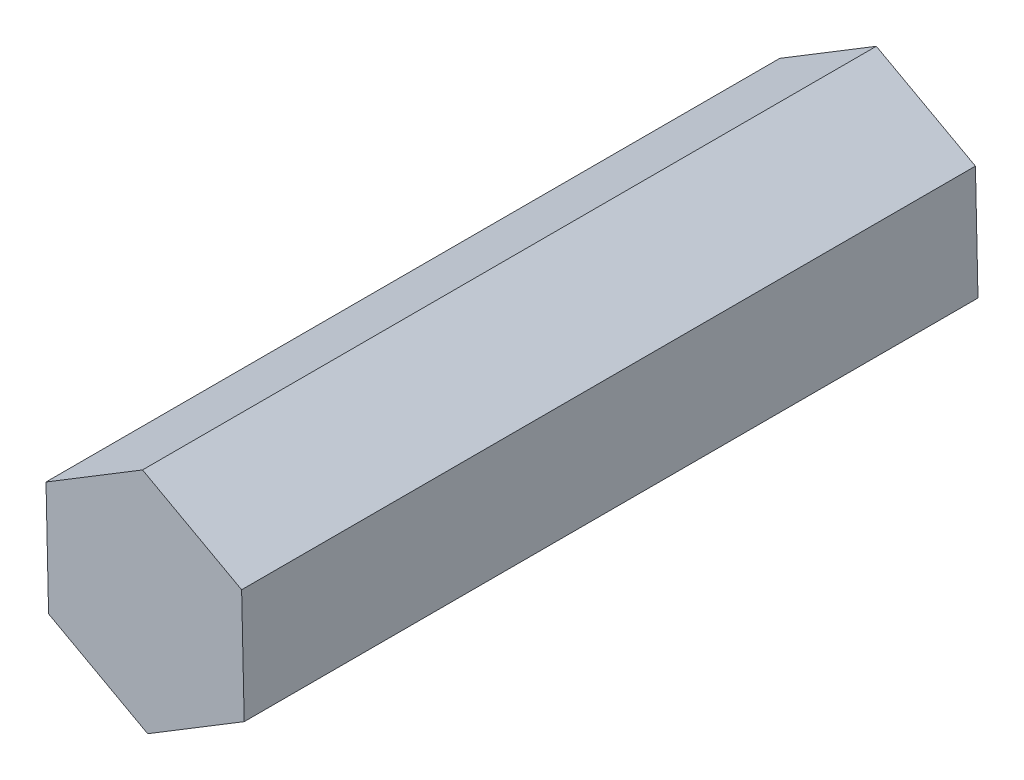
SolidWorks part; units mm, degrees
ref_plane "Front Plane" through (0, 0, 0) normal (0, 0, 1) x (1, 0, 0)
ref_plane "Top Plane" through (0, 0, 0) normal (0, 1, 0) x (1, 0, 0)
ref_plane "Right Plane" through (0, 0, 0) normal (1, 0, 0) x (0, 0, -1)
sketch "Sketch1" plane through (0, 0, 0) normal (0, 0, 1) x (1, 0, 0)
  line L1 (-6.4322, 3.52) -> (-6.2645, -3.8105)
  line L2 (-6.2645, -3.8105) -> (0.1677, -7.3304)
  line L3 (0.1677, -7.3304) -> (6.4322, -3.52)
  line L4 (6.4322, -3.52) -> (6.2645, 3.8105)
  line L5 (6.2645, 3.8105) -> (-0.1677, 7.3304)
  line L6 (-0.1677, 7.3304) -> (-6.4322, 3.52)
  circle A0 centre (0, 0) radius 6.35 construction
  dimension "D1" = 12.7
extrude "Boss-Extrude1" add sketch "Sketch1" along normal blind 47.625
